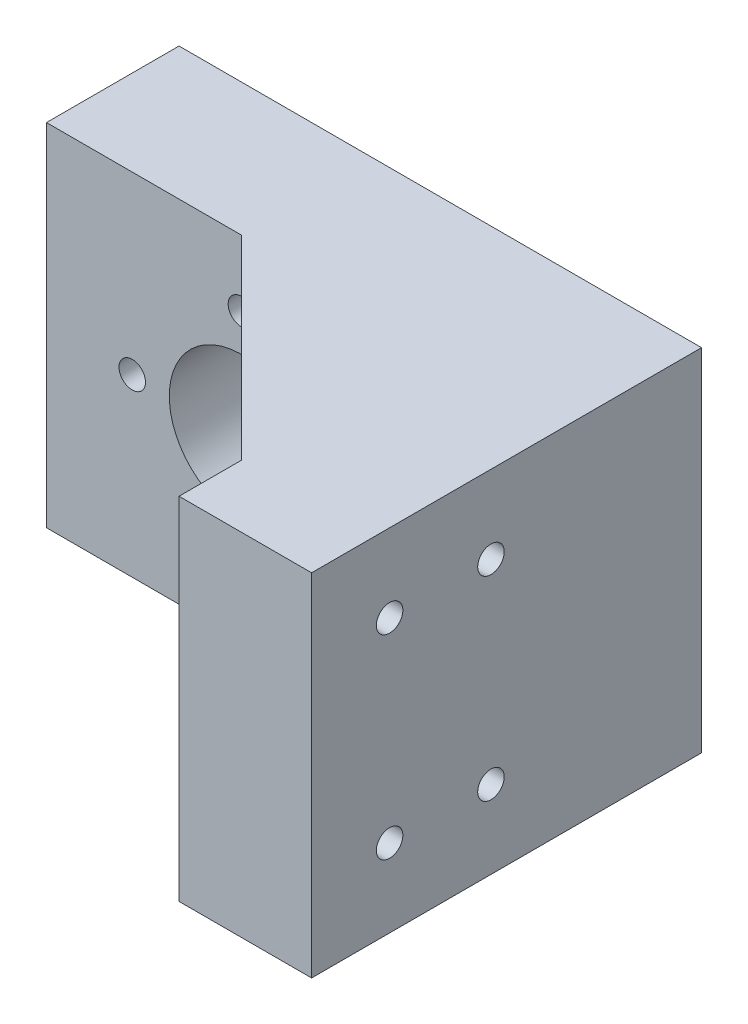
SolidWorks part; units mm, degrees
material "PLA"
ref_plane "Front Plane" through (0, 0, 0) normal (1, 0, 0) x (0, 1, 0)
ref_plane "Top Plane" through (0, 0, 0) normal (0, 0, 1) x (0, 1, 0)
ref_plane "Right Plane" through (0, 0, 0) normal (0, 1, 0) x (-1, 0, 0)
sketch "Sketch1" plane through (0, 0, 0) normal (0, 1, 0) x (-1, 0, 0)
  line L0 (-33.5, 50) -> (-16.5, 50)
  line L1 (-16.5, 50) -> (-16.5, 17)
  line L2 (-16.5, 17) -> (33.5, 17)
  line L3 (33.5, 17) -> (33.5, 0)
  line L4 (33.5, 0) -> (-33.5, 0)
  line L5 (-33.5, 0) -> (-33.5, 50)
  point P2 (0, 0)
  dimension "D1" = 17
  dimension "D2" = 67
  dimension "D3" = 50
  dimension "D4" = 17
extrude "Boss-Extrude1" add sketch "Sketch1" against normal mid plane 45
sketch "Sketch2" plane through (0, 0, 17) normal (0, 0, 1) x (1, 0, 0)
  line L0 (-8.5, 22.5) -> (-8.5, -22.5) construction
  line L1 (-33.5, 22.5) -> (16.5, 22.5) construction
  line L2 (-33.5, -22.5) -> (16.5, -22.5) construction
  line L3 (-33.5, 0) -> (16.5, 0) construction
  line L6 (-33.5, -22.5) -> (-33.5, 22.5) construction
  line L7 (16.5, -22.5) -> (16.5, 22.5) construction
  circle A6 centre (-8.5, 0) radius 9.25
  circle A7 centre (-8.5, 14) radius 1.7
  circle A8 centre (5.5, 0) radius 1.7
  circle A9 centre (-8.5, -14) radius 1.7
  circle A10 centre (-22.5, 0) radius 1.7
  dimension "D1" = 18.5
  dimension "D2" = 3.4
  dimension "D4" = 4
  dimension "D3" = 14
extrude "Cut-Extrude1" cut sketch "Sketch2" against normal through all
sketch "Sketch3" plane through (16.5, 0, 0) normal (-1, 0, 0) x (0, -1, 0)
  line L0 (0, 50) -> (0, 17) construction
  line L3 (22.5, 50) -> (-22.5, 50) construction
  line L6 (22.5, 17) -> (-22.5, 17) construction
  line L7 (-22.5, 33.5) -> (22.5, 33.5) construction
  line L8 (-22.5, 17) -> (-22.5, 50) construction
  line L9 (22.5, 17) -> (22.5, 50) construction
  circle A0 centre (12.5, 40) radius 1.7
  circle A1 centre (-12.5, 40) radius 1.7
  circle A2 centre (12.5, 27) radius 1.7
  circle A3 centre (-12.5, 27) radius 1.7
  dimension "D1" = 3.4
  dimension "D6" = 3.4
  dimension "D2" = 10
  dimension "D3" = 10
  dimension "D4" = 10
  dimension "D5" = 10
extrude "Cut-Extrude2" cut sketch "Sketch3" against normal through all
sketch "Sketch8" plane through (0, 22.5, 0) normal (0, 1, 0) x (-1, 0, 0)
  line L0 (-16.5, 42) -> (8.5, 17)
  line L1 (-16.5, 17) -> (-16.5, 50) construction
  line L2 (33.5, 17) -> (-16.5, 17) construction
  line L3 (8.5, 17) -> (-16.5, 17)
  line L4 (-16.5, 17) -> (-16.5, 42)
  dimension "D1" = 25
  dimension "D2" = 25
extrude "Boss-Extrude4" add sketch "Sketch8" against normal blind 5
sketch "Sketch9" plane through (0, -22.5, 0) normal (0, -1, 0) x (1, 0, 0)
  line L0 (-8.5, 17) -> (16.5, 17)
  line L1 (-33.5, 17) -> (16.5, 17) construction
  line L2 (16.5, 17) -> (-8.5, 17) construction
  line L3 (16.5, 17) -> (16.5, 42)
  line L4 (16.5, 42) -> (-8.5, 17)
  dimension "D1" = 25
  dimension "D2" = 25
extrude "Boss-Extrude5" add sketch "Sketch9" against normal blind 5
